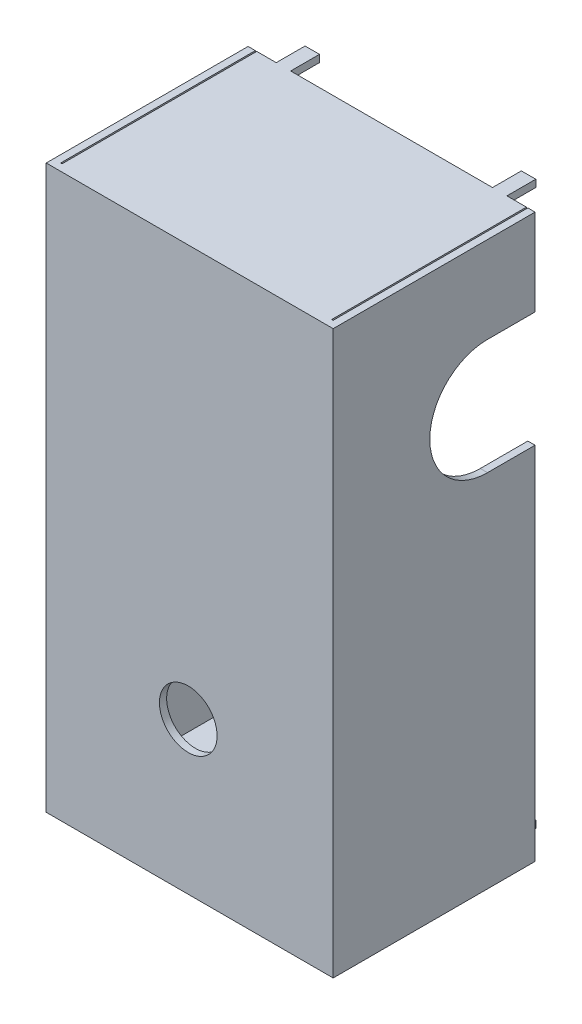
SolidWorks part; units mm, degrees
material "Aluminium"
ref_plane "Plan de face" through (0, 0, 0) normal (0, 0, 1) x (1, 0, 0)
ref_plane "Plan de dessus" through (0, 0, 0) normal (0, 1, 0) x (1, 0, 0)
ref_plane "Plan de droite" through (0, 0, 0) normal (1, 0, 0) x (0, 0, -1)
sketch "Esquisse1" plane through (0, 0, 0) normal (0, 0, 1) x (1, 0, 0)
  line L0 (-81.0423, 24.2361) -> (-81.0423, -14.7639)
  line L1 (-81.0423, 24.2361) -> (-80.5423, 24.2361)
  line L2 (-81.0423, -14.7639) -> (-80.5423, -14.7639)
  line L3 (-80.5423, 24.2361) -> (-80.5423, -14.7639)
  line L8 (-80.4423, 24.2361) -> (-80.4423, 23.7361)
  line L9 (-80.4423, 24.2361) -> (-61.7423, 24.2361)
  line L10 (-80.4423, 23.7361) -> (-61.7423, 23.7361)
  line L11 (-61.7423, 24.2361) -> (-61.7423, 23.7361)
  line L13 (-61.6423, 24.2361) -> (-61.6423, -14.7639)
  line L14 (-61.6423, 24.2361) -> (-61.1423, 24.2361)
  line L15 (-61.6423, -14.7639) -> (-61.1423, -14.7639)
  line L16 (-61.1423, 24.2361) -> (-61.1423, -14.7639)
  line L18 (-80.4423, -14.2639) -> (-80.4423, -14.7639)
  line L19 (-80.4423, -14.2639) -> (-61.7423, -14.2639)
  line L20 (-80.4423, -14.7639) -> (-61.7423, -14.7639)
  line L21 (-61.7423, -14.2639) -> (-61.7423, -14.7639)
  dimension "D1" = 0.5
  dimension "D2" = 39
  dimension "D3" = 19.9
  dimension "D5" = 0.1
  dimension "D6" = 0.5
  dimension "D8" = 0.1
  dimension "D9" = 0.5
  dimension "D11" = 0.5
  dimension "D12" = 0.1
  dimension "D13" = 0.1
extrude "Extrusion1" add sketch "Esquisse1" along normal blind 13.5
sketch "Esquisse2" plane through (0, 0, 13.5) normal (0, 0, 1) x (1, 0, 0)
  line L0 (-81.0423, 24.2361) -> (-81.0423, -14.7639)
  line L1 (-81.0423, 24.2361) -> (-61.1423, 24.2361)
  line L2 (-81.0423, -14.7639) -> (-61.1423, -14.7639)
  line L3 (-61.1423, 24.2361) -> (-61.1423, -14.7639)
  line L4 (-61.1423, -14.7639) -> (-61.1423, 24.2361) construction
extrude "Extrusion2" add sketch "Esquisse2" along normal blind 0.5
sketch "Esquisse3" plane through (-61.1423, 0, 0) normal (1, 0, 0) x (0, 0, -1)
  line L0 (0, 18.2361) -> (0, 10.2361)
  line L1 (0, 18.2361) -> (-3.3, 18.2361)
  line L2 (0, 10.2361) -> (-3.3, 10.2361)
  line L4 (0, -14.7639) -> (0, 24.2361) construction
  line L5 (-3.3, 14.2361) -> (4.9469, 14.2361) construction
  line L6 (-14, 24.2361) -> (0, 24.2361) construction
  line L10 (-3.3, -4.7639) -> (2.907, -4.7639) construction
  arc A0 (-3.3, 18.2361) -> (-3.3, 10.2361) centre (-3.3, 14.2361) ccw
  dimension "D2" = 8
  dimension "D3" = 10
  dimension "D5" = 19
extrude "Enlèv. mat.-Extru.1" cut sketch "Esquisse3" against normal blind 10
sketch "Esquisse4" plane through (0, 0, 0) normal (0, 0, -1) x (-1, 0, 0)
  line L0 (63.0923, 24.2361) -> (63.0923, 23.7361)
  line L1 (63.0923, 24.2361) -> (64.0923, 24.2361)
  line L2 (63.0923, 23.7361) -> (64.0923, 23.7361)
  line L3 (64.0923, 24.2361) -> (64.0923, 23.7361)
  line L6 (78.0923, 24.2361) -> (78.0923, 23.7361)
  line L7 (78.0923, 24.2361) -> (79.0923, 24.2361)
  line L8 (78.0923, 23.7361) -> (79.0923, 23.7361)
  line L9 (79.0923, 24.2361) -> (79.0923, 23.7361)
  line L11 (71.0923, 24.2361) -> (71.0923, 22.3484) construction
  line L12 (63.0923, -14.2639) -> (63.0923, -14.7639)
  line L13 (63.0923, -14.2639) -> (64.0923, -14.2639)
  line L14 (63.0923, -14.7639) -> (64.0923, -14.7639)
  line L15 (64.0923, -14.2639) -> (64.0923, -14.7639)
  line L16 (61.1423, 18.2361) -> (61.1423, 24.2361) construction
  line L17 (81.0423, 24.2361) -> (81.0423, -14.7639) construction
  line L20 (79.0923, -14.2639) -> (79.0923, -14.7639)
  line L21 (79.0923, -14.2639) -> (78.0923, -14.2639)
  line L22 (79.0923, -14.7639) -> (78.0923, -14.7639)
  line L23 (78.0923, -14.2639) -> (78.0923, -14.7639)
  dimension "D1" = 1
  dimension "D2" = 16
extrude "Extrusion3" add sketch "Esquisse4" along normal blind 2
sketch "Esquisse5" plane through (0, 0, 14) normal (0, 0, 1) x (1, 0, 0)
  circle A0 centre (-71.1923, -4.2481) radius 2
  dimension "D1" = 4
extrude "Enlèv. mat.-Extru.2" cut sketch "Esquisse5" against normal blind 2
